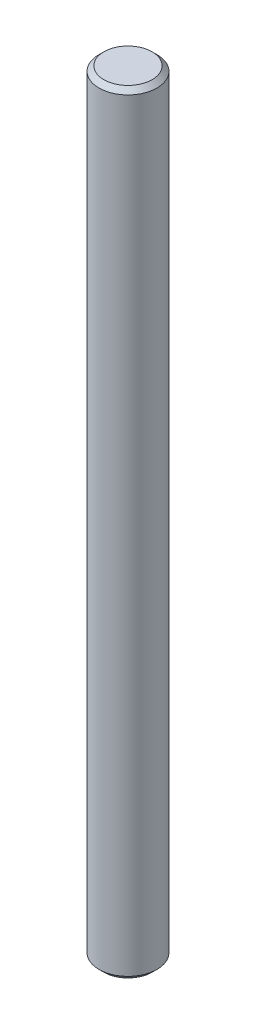
SolidWorks part; units mm, degrees
material "AISI 304"
ref_plane "Front Plane" through (0, 0, 0) normal (0, 0, 1) x (1, 0, 0)
ref_plane "Top Plane" through (0, 0, 0) normal (0, 1, 0) x (1, 0, 0)
ref_plane "Right Plane" through (0, 0, 0) normal (1, 0, 0) x (0, 0, -1)
sketch "Sketch2" plane through (0, 0, 0) normal (0, 1, 0) x (1, 0, 0)
  circle A0 centre (0, 0) radius 1.5
  dimension "D1" = 3
extrude "Boss-Extrude1" add sketch "Sketch2" along normal blind 40
chamfer "Chamfer1" distance 0.25 angle 45 2 edges at (0, 0, 1.5) (0, 40, 1.5)
